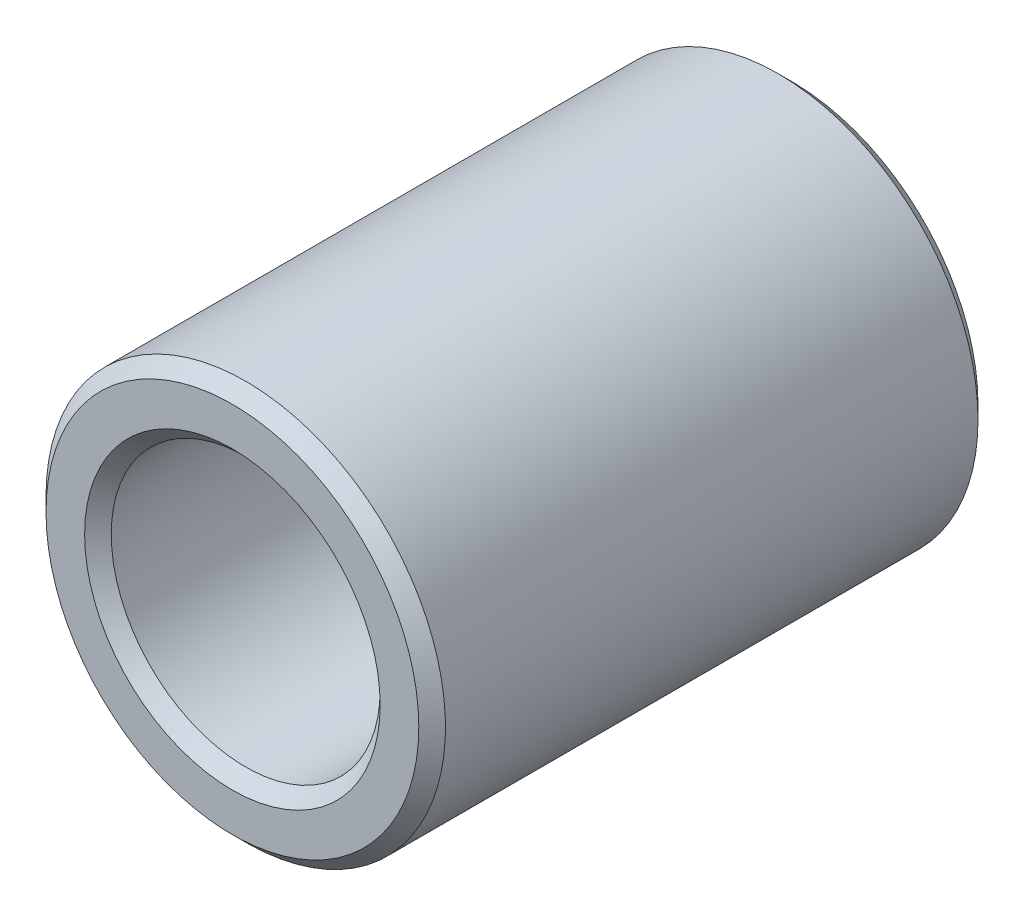
SolidWorks part; units mm, degrees
ref_plane "Plano frontal" through (0, 0, 0) normal (0, 0, 1) x (1, 0, 0)
ref_plane "Plano superior" through (0, 0, 0) normal (0, 1, 0) x (1, 0, 0)
ref_plane "Plano direito" through (0, 0, 0) normal (1, 0, 0) x (0, 0, -1)
sketch "Esboço1" plane through (0, 0, 0) normal (0, 0, 1) x (1, 0, 0)
  circle A0 centre (0, 0) radius 5.05
  circle A1 centre (0, 0) radius 7.5
  dimension "D1" = 10.1
  dimension "D2" = 15
extrude "Ressalto-extrusão1" add sketch "Esboço1" along normal mid plane 21
chamfer "Chanfro1" distance 0.5 angle 45 4 edges at (5.05, 0, -10.5) (7.5, 0, -10.5) (5.05, 0, 10.5) (7.5, 0, 10.5)
